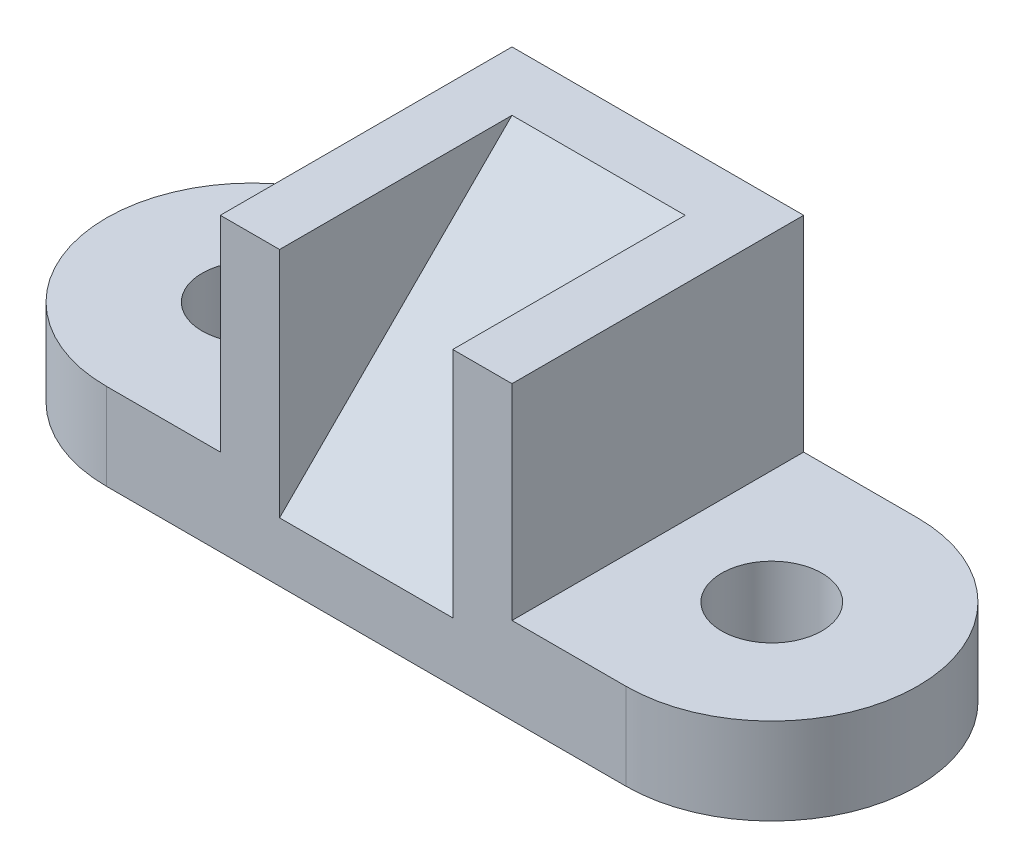
SolidWorks part; units mm, degrees
ref_plane "Front Plane" through (0, 0, 0) normal (0, 0, 1) x (1, 0, 0)
ref_plane "Top Plane" through (0, 0, 0) normal (0, 1, 0) x (1, 0, 0)
ref_plane "Right Plane" through (0, 0, 0) normal (1, 0, 0) x (0, 0, -1)
sketch "Sketch2" plane through (0, 0, 0) normal (0, 1, 0) x (1, 0, 0)
  line L1 (-57, 32) -> (57, 32)
  line L2 (-57, 32) -> (-57, -32) construction
  line L3 (-57, -32) -> (57, -32)
  line L4 (57, 32) -> (57, -32) construction
  line L5 (-57, 32) -> (57, -32) construction
  line L6 (-57, -32) -> (57, 32) construction
  arc A0 (-57, 32) -> (-57, -32) centre (-57, 0) ccw
  arc A1 (57, -32) -> (57, 32) centre (57, 0) ccw
  circle A2 centre (-57, 0) radius 11
  circle A3 centre (57, 0) radius 11
  point P0 (0, 0)
  dimension "D3" = 22
  dimension "D4" = 22
  dimension "D1" = 114
  dimension "D2" = 64
extrude "Boss-Extrude1" add sketch "Sketch2" along normal blind 19
sketch "Sketch3" plane through (0, 19, 0) normal (0, 1, 0) x (1, 0, 0)
  line L0 (-57, -32) -> (57, -32) construction
  line L2 (-32, 32) -> (32, 32)
  line L3 (-32, 32) -> (-32, -32)
  line L4 (-32, -32) -> (32, -32)
  line L5 (32, 32) -> (32, -32)
  line L6 (-32, 32) -> (32, -32) construction
  line L7 (-32, -32) -> (32, 32) construction
  point P1 (0, 0)
  dimension "D1" = 64
extrude "Boss-Extrude2" add sketch "Sketch3" along normal blind 45
sketch "Sketch4" plane through (0, 64, 0) normal (0, 1, 0) x (1, 0, 0)
  line L10 (19, -32) -> (-19, -32)
  line L13 (19, -32) -> (19, 19)
  line L14 (19, 19) -> (-19, 19)
  line L15 (-19, 19) -> (-19, -32)
  line L16 (19, -32) -> (19, 19)
  line L17 (19, 19) -> (-19, 19)
  line L18 (-19, 19) -> (-19, -32)
  dimension "D1" = 13
extrude "Cut-Extrude1" cut sketch "Sketch4" against normal blind 51
sketch "Sketch5" plane through (-19, 0, 0) normal (1, 0, 0) x (0, 0, -1)
  line L0 (-32, 13) -> (19, 64)
  line L1 (19, 64) -> (19, 13)
  line L2 (-32, 13) -> (19, 13)
extrude "Boss-Extrude3" add sketch "Sketch5" along normal up to surface (38 mm away) up to face at (19, 38.5, 6.5)
